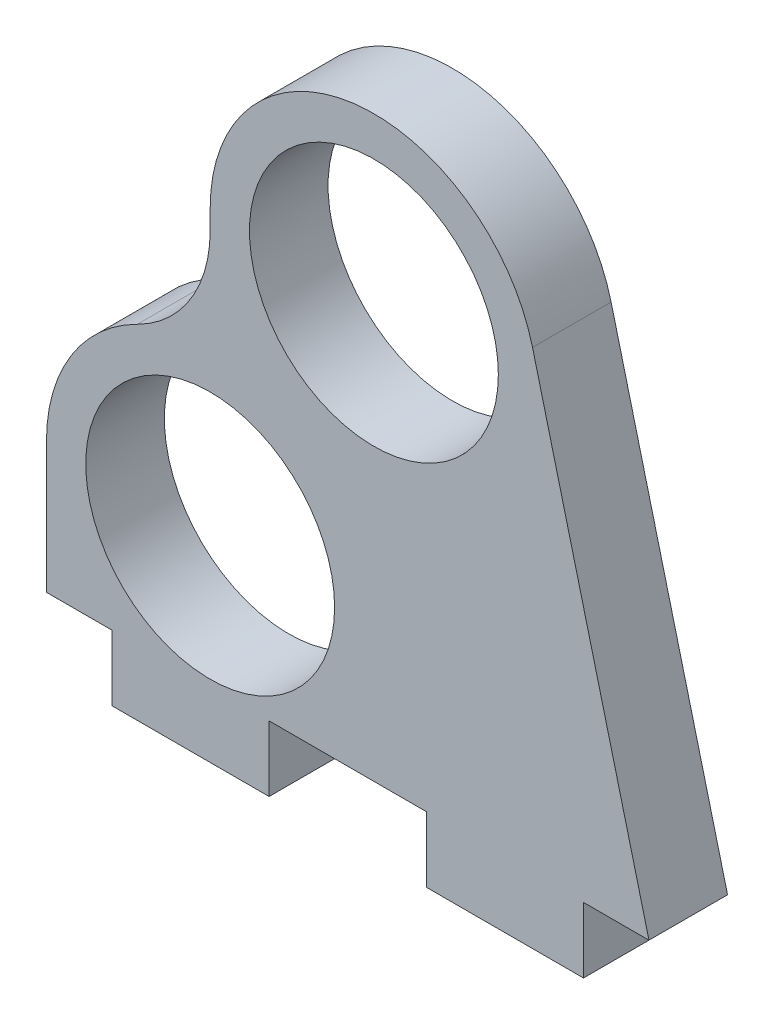
SolidWorks part; units mm, degrees
ref_plane "Alzado" through (0, 0, 0) normal (0, 0, 1) x (1, 0, 0)
ref_plane "Planta" through (0, 0, 0) normal (0, 1, 0) x (1, 0, 0)
ref_plane "Vista lateral" through (0, 0, 0) normal (1, 0, 0) x (0, 0, -1)
sketch "Croquis1" plane through (0, 0, 0) normal (0, 0, 1) x (1, 0, 0)
  line L0 (-12.5, 0) -> (-12.5, -10)
  line L1 (0, 0) -> (12.5, 21.6506) construction
  line L3 (-12.5, -10) -> (-7.5, -10) construction
  line L5 (4.5, -15) -> (-7.5, -15)
  line L6 (28.5, -15) -> (16.5, -15)
  line L9 (-12.5, -10) -> (-7.5, -10)
  line L10 (-7.5, -15) -> (-7.5, -10)
  line L14 (28.5, -15) -> (28.5, -10)
  line L16 (16.5, -15) -> (16.5, -10)
  line L17 (16.5, -10) -> (4.5, -10)
  line L18 (4.5, -15) -> (4.5, -10)
  line L19 (12.5, 21.6506) -> (0, 21.6506) construction
  line L20 (0, 21.6506) -> (0, 20.1556)
  line L21 (28.5, -10) -> (33.5, -10)
  line L23 (4.5, -10) -> (16.5, -10) construction
  line L24 (33.5, -10) -> (24.61, 24.7488)
  arc A0 (-5.5556, 11.1976) -> (-12.5, 0) centre (0, 0) ccw
  circle A1 centre (0, 0) radius 9.5
  arc A2 (24.61, 24.7488) -> (0, 21.6506) centre (12.5, 21.6506) ccw
  circle A3 centre (12.5, 21.6506) radius 9.5
  arc A5 (0, 20.1556) -> (-5.5556, 11.1976) centre (-10, 20.1556) cw
  point P14 (0, 12.5)
  dimension "D1" = 19
  dimension "D2" = 25
  dimension "D4" = 19
  dimension "D5" = 25
  dimension "D8" = 10
  dimension "D3" = 25
  dimension "D6" = 10
  dimension "D7" = 60
  dimension "D9" = 5
  dimension "D10" = 5
  dimension "D11" = 12
  dimension "D12" = 12
  dimension "D13" = 12
  dimension "D14" = 5
extrude "Saliente-Extruir1" add sketch "Croquis1" along normal blind 6
